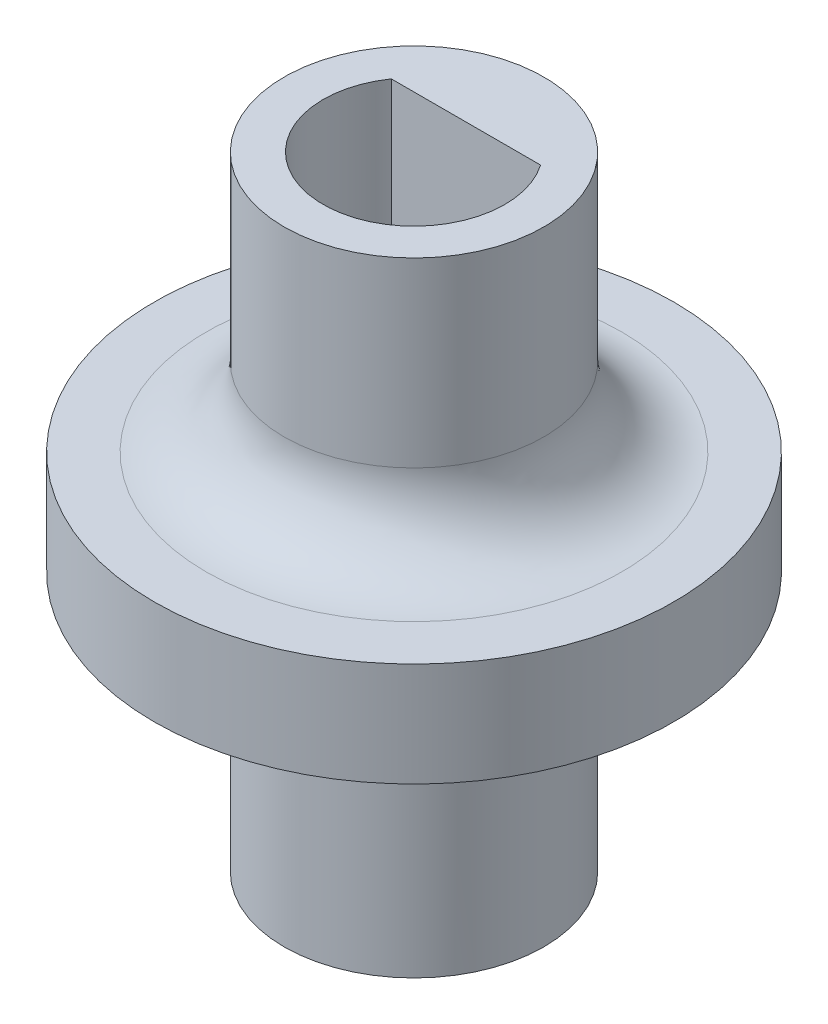
SolidWorks part; units mm, degrees
ref_plane "Alzado" through (0, 0, 0) normal (0, 0, 1) x (1, 0, 0)
ref_plane "Planta" through (0, 0, 0) normal (0, 1, 0) x (1, 0, 0)
ref_plane "Vista lateral" through (0, 0, 0) normal (1, 0, 0) x (0, 0, -1)
sketch "Croquis1" plane through (0, 0, 0) normal (0, 1, 0) x (1, 0, 0)
  circle A0 centre (0, 0) radius 10
  dimension "D1" = 20
extrude "Saliente-Extruir1" add sketch "Croquis1" along normal mid plane 4
sketch "Croquis2" plane through (0, 2, 0) normal (0, 1, 0) x (1, 0, 0)
  circle A0 centre (0, 0) radius 5
  dimension "D1" = 10
extrude "Saliente-Extruir2" add sketch "Croquis2" along normal blind 10
sketch "Croquis3" plane through (0, 12, 0) normal (0, 1, 0) x (1, 0, 0)
  line L0 (0, -3.5) -> (0, 2) construction
  line L1 (-2.8723, 2) -> (2.8723, 2)
  arc A0 (-2.8723, 2) -> (2.8723, 2) centre (0, 0) ccw
  dimension "D1" = 5.5
  dimension "D2" = 3.5
extrude "Cortar-Extruir1" cut sketch "Croquis3" against normal blind 8
sketch "Croquis4" plane through (0, -2, 0) normal (0, -1, 0) x (-1, 0, 0)
  circle A0 centre (0, 0) radius 5
  dimension "D1" = 10
extrude "Saliente-Extruir3" add sketch "Croquis4" along normal blind 10
fillet "Redondeo1" radius 3 2 edges at (0, -2, -5) (0, 2, 5)
sketch "Croquis5" plane through (0, -12, 0) normal (0, -1, 0) x (1, 0, 0)
  line L0 (0, 2.4) -> (0, -2.4) construction
  line L1 (-2.1915, 2.4) -> (2.1915, 2.4)
  line L2 (-2.1915, -2.4) -> (2.1915, -2.4)
  arc A0 (-2.1915, 2.4) -> (-2.1915, -2.4) centre (0, 0) ccw
  arc A1 (2.1915, -2.4) -> (2.1915, 2.4) centre (0, 0) ccw
  point P5 (0, 0)
  dimension "D1" = 4.8
  dimension "D2" = 3.25
extrude "Cortar-Extruir2" cut sketch "Croquis5" against normal blind 9
